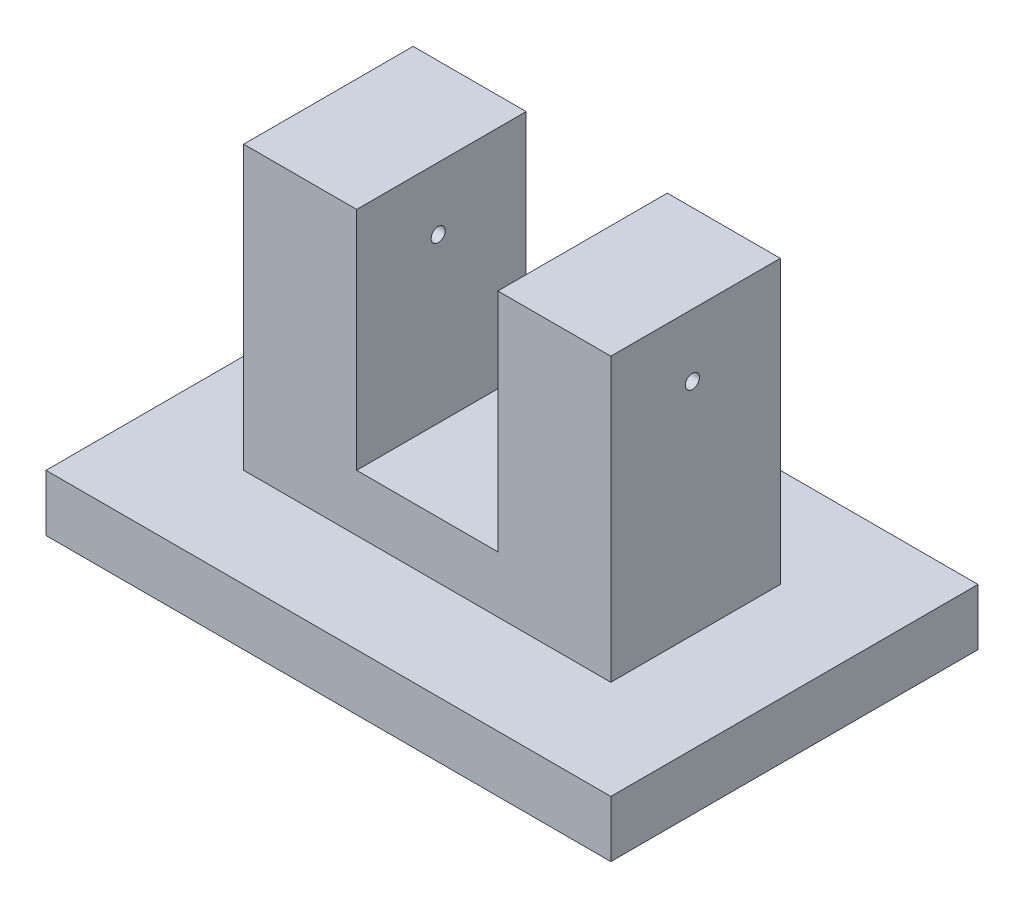
SolidWorks part; units mm, degrees
ref_plane "前视基准面" through (0, 0, 0) normal (0, 0, 1) x (1, 0, 0)
ref_plane "上视基准面" through (0, 0, 0) normal (0, 1, 0) x (1, 0, 0)
ref_plane "右视基准面" through (0, 0, 0) normal (1, 0, 0) x (0, 0, -1)
sketch "草图1" plane through (0, 0, 0) normal (0, 1, 0) x (1, 0, 0)
  line L1 (-14.0203, 8.8007) -> (5.9797, 8.8007)
  line L2 (-14.0203, 8.8007) -> (-14.0203, -4.1993)
  line L3 (-14.0203, -4.1993) -> (5.9797, -4.1993)
  line L4 (5.9797, 8.8007) -> (5.9797, -4.1993)
  line L5 (-4.0203, -4.1993) -> (-4.0203, 8.8007) construction
  line L6 (-14.0203, 2.3007) -> (5.9797, 2.3007) construction
  point P0 (-4.0203, 2.3007)
  dimension "D1" = 20
  dimension "D2" = 13
extrude "凸台-拉伸1" add sketch "草图1" along normal blind 2
sketch "草图2" plane through (0, 2, 0) normal (0, 1, 0) x (1, 0, 0)
  line L0 (-4.0203, 8.8007) -> (-4.0203, -4.1993) construction
  line L1 (5.9797, 8.8007) -> (-14.0203, 8.8007) construction
  line L2 (-14.0203, -4.1993) -> (5.9797, -4.1993) construction
  line L3 (-14.0203, 2.3007) -> (5.9797, 2.3007) construction
  line L4 (-14.0203, 8.8007) -> (-14.0203, -4.1993) construction
  line L5 (5.9797, -4.1993) -> (5.9797, 8.8007) construction
  line L7 (-10.5203, 5.3007) -> (2.4797, 5.3007)
  line L8 (-10.5203, 5.3007) -> (-10.5203, -0.6993)
  line L9 (-10.5203, -0.6993) -> (2.4797, -0.6993)
  line L10 (2.4797, 5.3007) -> (2.4797, -0.6993)
  line L11 (-4.0203, -0.6993) -> (-4.0203, 5.3007) construction
  line L12 (-10.5203, 2.3007) -> (2.4797, 2.3007) construction
  point P12 (-4.0203, 2.3007)
  dimension "D1" = 13
  dimension "D2" = 6
extrude "凸台-拉伸2" add sketch "草图2" along normal blind 2
sketch "草图3" plane through (0, 4, 0) normal (0, 1, 0) x (1, 0, 0)
  line L0 (-10.5203, -0.6993) -> (2.4797, -0.6993) construction
  line L1 (-10.5203, 5.3007) -> (-6.5203, 5.3007)
  line L2 (-10.5203, 5.3007) -> (-10.5203, -0.6993)
  line L3 (-10.5203, -0.6993) -> (-6.5203, -0.6993)
  line L4 (-6.5203, 5.3007) -> (-6.5203, -0.6993)
  line L5 (-10.5203, 5.3007) -> (-6.5203, -0.6993) construction
  line L6 (-10.5203, -0.6993) -> (-6.5203, 5.3007) construction
  line L8 (2.4797, -0.6993) -> (-1.5203, -0.6993)
  line L9 (2.4797, -0.6993) -> (2.4797, 5.3007)
  line L10 (2.4797, 5.3007) -> (-1.5203, 5.3007)
  line L11 (-1.5203, -0.6993) -> (-1.5203, 5.3007)
  line L12 (2.4797, -0.6993) -> (-1.5203, 5.3007) construction
  line L13 (2.4797, 5.3007) -> (-1.5203, -0.6993) construction
  point P4 (-8.5203, 2.3007)
  point P12 (0.4797, 2.3007)
  dimension "D1" = 4
  dimension "D2" = 4
  dimension "D3" = 6
extrude "凸台-拉伸3" add sketch "草图3" along normal blind 8
sketch "草图4" plane through (-10.5203, 0, 0) normal (-1, 0, 0) x (0, 0, 1)
  circle A0 centre (-2.1877, 9.784) radius 0.25
  point P2 (-2.1877, 9.784)
  dimension "D1" = 0.5
extrude "切除-拉伸1" cut sketch "草图4" against normal through all
